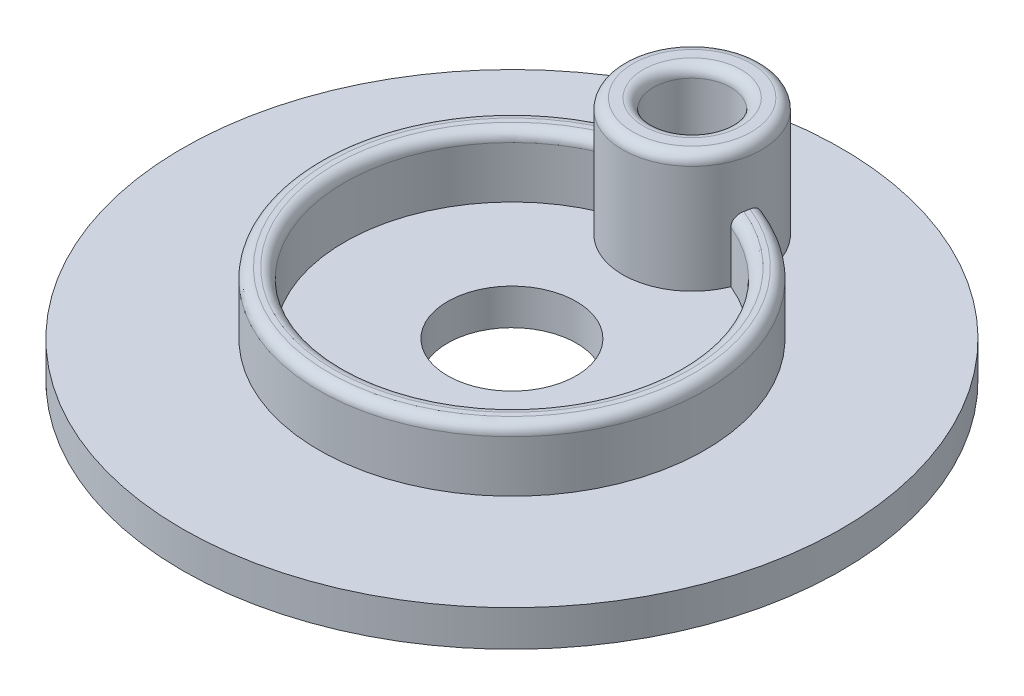
SolidWorks part; units mm, degrees
ref_plane "前视基准面" through (0, 0, 0) normal (0, 0, 1) x (1, 0, 0)
ref_plane "上视基准面" through (0, 0, 0) normal (0, 1, 0) x (1, 0, 0)
ref_plane "右视基准面" through (0, 0, 0) normal (1, 0, 0) x (0, 0, -1)
other "Configuration Table"
sketch "草图4" plane through (0, 0, 0) normal (0, 1, 0) x (1, 0, 0)
  circle A0 centre (0, 0) radius 64
  dimension "D1" = 128
extrude "凸台-拉伸1" add sketch "草图4" along normal blind 7
sketch "草图5" plane through (0, 7, 0) normal (0, 1, 0) x (1, 0, 0)
  circle A0 centre (0, 0) radius 37.5
  circle A1 centre (0, 0) radius 32.5
  circle A2 centre (0, 0) radius 37.5
  dimension "D1" = 75
  dimension "D2" = 5
  dimension "D3" = 5
extrude "凸台-拉伸2" add sketch "草图5" along normal blind 12 contours A0 A1
sketch "草图7" plane through (0, 7, 0) normal (0, 1, 0) x (1, 0, 0)
  circle A0 centre (0, 0) radius 12.5
  dimension "D1" = 25
extrude "切除-拉伸1" cut sketch "草图7" against normal through all
fillet "圆角1" radius 2 2 edges at (0, 19, 37.5) (0, 19, 32.5)
sketch "草图10" plane through (0, 0, 0) normal (0, 1, 0) x (1, 0, 0)
  line L0 (0, 0) -> (0, 35) construction
  circle A0 centre (0, 35) radius 13.5
  dimension "D1" = 27
  dimension "D2" = 35
extrude "凸台-拉伸3" add sketch "草图10" along normal blind 30
sketch "草图11" plane through (0, 30, 0) normal (0, 1, 0) x (1, 0, 0)
  circle A0 centre (0, 35) radius 7.5
  dimension "D1" = 15
extrude "切除-拉伸2" cut sketch "草图11" against normal through all
fillet "圆角2" radius 2 2 edges at (0, 30, -21.5) (0, 30, -27.5)
